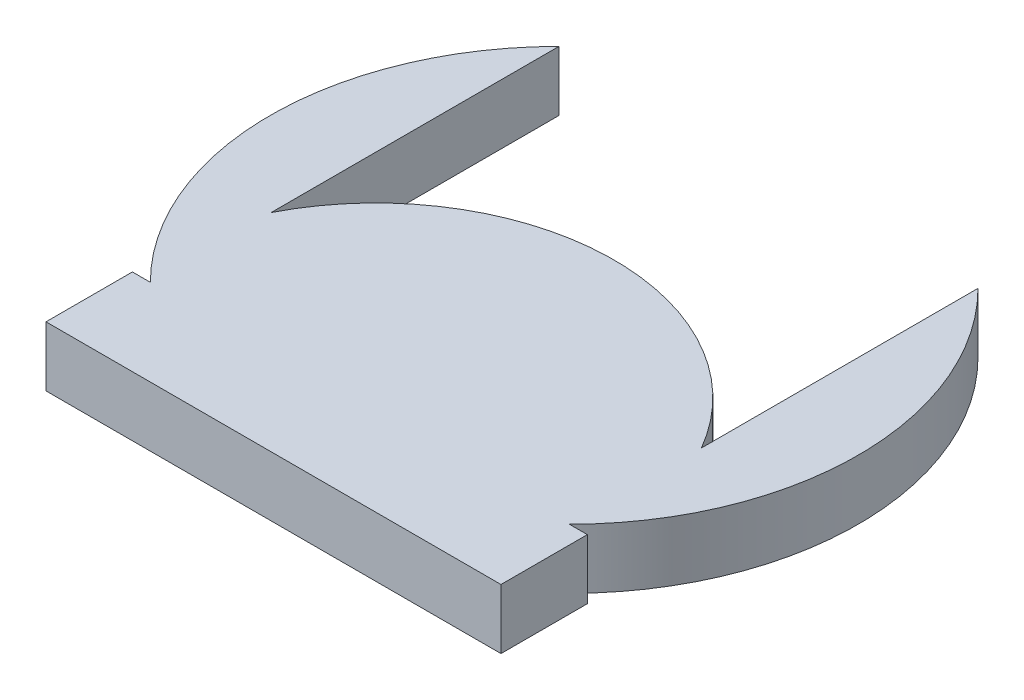
SolidWorks part; units mm, degrees
ref_plane "Front Plane" through (0, 0, 0) normal (0, 0, 1) x (1, 0, 0)
ref_plane "Top Plane" through (0, 0, 0) normal (0, 1, 0) x (1, 0, 0)
ref_plane "Right Plane" through (0, 0, 0) normal (1, 0, 0) x (0, 0, -1)
sketch "Sketch1" plane through (0, 0, 0) normal (0, 1, 0) x (1, 0, 0)
  line L0 (0, 0) -> (-35, 0) construction
  line L1 (-17.5, 0) -> (-17.5, 35.5876) construction
  line L2 (-35, 34.1269) -> (-35, 10.092)
  line L3 (0, 34.1269) -> (0, 10.092)
  arc A0 (-35, 0) -> (-35, 34.1269) centre (-17.9365, 17.0635) cw
  arc A1 (0, 0) -> (0, 34.1269) centre (-17.0635, 17.0635) ccw
  arc A2 (-35, 10.092) -> (0, 11.0215) centre (-17.248, 1.0689) cw
  arc A3 (-35, 0) -> (0, 0) centre (-17.5, 54.6637) ccw
  dimension "D1" = 35
extrude "Boss-Extrude2" add sketch "Sketch1" along normal blind 5
sketch "Sketch4" plane through (0, 5, 0) normal (0, 1, 0) x (1, 0, 0)
  line L0 (0, 0) -> (0, -7.2151)
  line L1 (0, -7.2151) -> (-35, -7.2151)
  line L2 (-35, -7.2151) -> (-35, 0)
  line L5 (0, 34.1269) -> (0, 11.0215)
  line L6 (-35, 10.092) -> (-35, 34.1269)
  line L7 (0, 34.1269) -> (0, 11.0215)
  line L8 (-35, 10.092) -> (-35, 34.1269)
  arc A4 (-35, 34.1269) -> (-35, 0) centre (-17.9365, 17.0635) ccw
  arc A5 (-35, 0) -> (0, 0) centre (-17.5, 54.6637) ccw
  arc A6 (0, 0) -> (0, 34.1269) centre (-17.0635, 17.0635) ccw
  arc A7 (0, 11.0215) -> (-35, 10.092) centre (-17.248, 1.0689) ccw
  arc A8 (-35, 34.1269) -> (-35, 0) centre (-17.9365, 17.0635) ccw
  arc A10 (0, 0) -> (0, 34.1269) centre (-17.0635, 17.0635) ccw
  arc A11 (0, 11.0215) -> (-35, 10.092) centre (-17.248, 1.0689) ccw
  dimension "D1" = 0
extrude "Boss-Extrude3" add sketch "Sketch4" against normal blind 5
sketch "Sketch5" plane through (0, 5, 0) normal (0, 1, 0) x (1, 0, 0)
  line L0 (-17.5, -7.2151) -> (-17.5, 2.5342) construction
  line L1 (-35, 0) -> (-36.5, 0)
  line L2 (-35, 0) -> (-35, -7.2151)
  line L3 (-35, -7.2151) -> (-36.5, -7.2151)
  line L4 (-36.5, 0) -> (-36.5, -7.2151)
  line L5 (-35, -7.2151) -> (0, -7.2151) construction
  line L6 (0, -7.2151) -> (1.5, -7.2151)
  line L7 (0, 0) -> (0, -7.2151)
  line L8 (0, 0) -> (1.5, 0)
  line L9 (1.5, 0) -> (1.5, -7.2151)
  dimension "D1" = 1.5
extrude "Boss-Extrude4" add sketch "Sketch5" against normal blind 5
